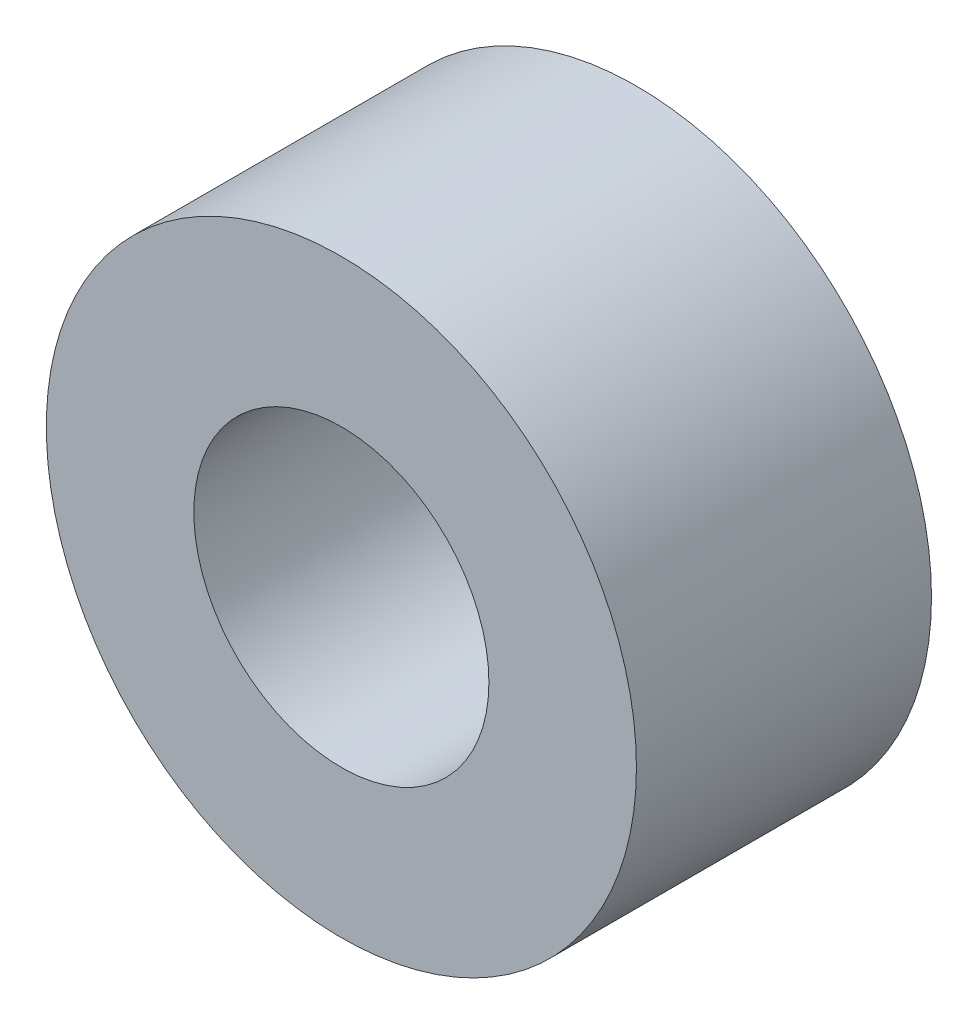
SolidWorks part; units mm, degrees
ref_plane "Front Plane" through (0, 0, 0) normal (0, 0, 1) x (1, 0, 0)
ref_plane "Top Plane" through (0, 0, 0) normal (0, 1, 0) x (1, 0, 0)
ref_plane "Right Plane" through (0, 0, 0) normal (1, 0, 0) x (0, 0, -1)
sketch "Sketch1" plane through (0, 0, 0) normal (0, 0, 1) x (1, 0, 0)
  circle A0 centre (0, 0) radius 5
  circle A1 centre (0, 0) radius 10
  dimension "D1" = 20
  dimension "D2" = 10
extrude "Boss-Extrude1" add sketch "Sketch1" along normal blind 10
